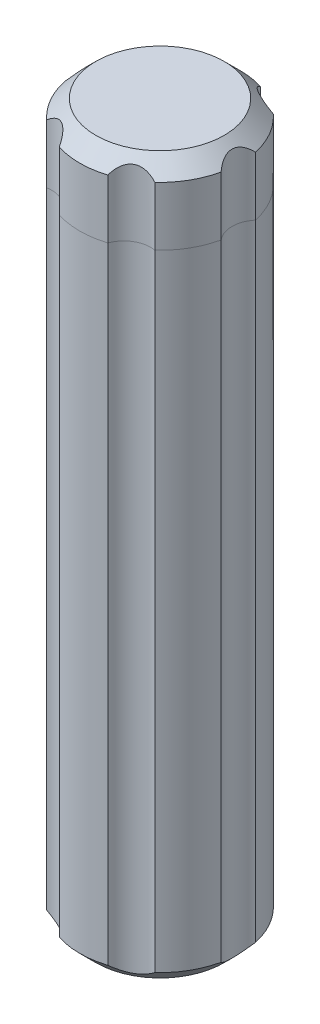
SolidWorks part; units mm, degrees
ref_plane "Front Plane" through (0, 0, 0) normal (0, 0, 1) x (1, 0, 0)
ref_plane "Top Plane" through (0, 0, 0) normal (0, 1, 0) x (1, 0, 0)
ref_plane "Right Plane" through (0, 0, 0) normal (1, 0, 0) x (0, 0, -1)
sketch "Sketch1" plane through (0, 0, 0) normal (0, 1, 0) x (1, 0, 0)
  circle A0 centre (0, 0) radius 7.5
  dimension "D1" = 15
extrude "Boss-Extrude1" add sketch "Sketch1" along normal blind 60
sketch "Sketch2" plane through (0, 60, 0) normal (0, 1, 0) x (1, 0, 0)
  circle A0 centre (0, 0) radius 6.1
  dimension "D1" = 12.2
extrude "Cut-Extrude1" cut sketch "Sketch2" against normal blind 58
sketch "Sketch3" plane through (0, 0, 0) normal (0, 0, 1) x (1, 0, 0)
  line L0 (-7.5, 0) -> (7.5, 0) construction
  circle A0 centre (0, 32) radius 3.5
  point P4 (0, 0)
  dimension "D1" = 7
  dimension "D2" = 32
extrude "Cut-Extrude2" cut sketch "Sketch3" against normal through all
sketch "Sketch4" plane through (0, 60, 0) normal (0, 1, 0) x (1, 0, 0)
  circle A0 centre (0, 0) radius 7.5
extrude "Boss-Extrude2" add sketch "Sketch4" along normal blind 7 separate body
sketch "Sketch5" plane through (0, 60, 0) normal (0, -1, 0) x (1, 0, 0)
  line L1 (2.9156, 5.05) -> (-2.9156, 5.05)
  line L2 (-2.9156, 5.05) -> (-5.8312, 0)
  line L3 (-5.8312, 0) -> (-2.9156, -5.05)
  line L4 (-2.9156, -5.05) -> (2.9156, -5.05)
  line L5 (2.9156, -5.05) -> (5.8312, 0)
  line L6 (5.8312, 0) -> (2.9156, 5.05)
  circle A0 centre (0, 0) radius 5.05 construction
  dimension "D1" = 10.1
extrude "Cut-Extrude3" cut sketch "Sketch5" against normal blind 4
chamfer "Chamfer1" distance 1.5 angle 45 1 edges at (0, 0, 7.5)
chamfer "Chamfer2" distance 1.5 angle 45 1 edges at (0, 67, 7.5)
sketch "Sketch7" plane through (0, 67, 0) normal (0, 1, 0) x (1, 0, 0)
  line L1 (4.6188, 8) -> (-4.6188, 8)
  line L2 (-4.6188, 8) -> (-9.2376, 0)
  line L3 (-9.2376, 0) -> (-4.6188, -8)
  line L4 (-4.6188, -8) -> (4.6188, -8)
  line L5 (4.6188, -8) -> (9.2376, 0)
  line L6 (9.2376, 0) -> (4.6188, 8)
  circle A0 centre (0, 0) radius 8 construction
  circle A1 centre (-9.2376, 0) radius 2.5
  circle A2 centre (-4.6188, 8) radius 2.5
  circle A3 centre (4.6188, 8) radius 2.5
  circle A4 centre (9.2376, 0) radius 2.5
  circle A5 centre (4.6188, -8) radius 2.5
  circle A6 centre (-4.6188, -8) radius 2.5
  dimension "D1" = 16
  dimension "D2" = 5
extrude "Cut-Extrude4" cut sketch "Sketch7" against normal blind 67 contours L2 A2 L1 | L3 A1 L2 | L4 A6 L3 | L5 A5 L4 | L6 A4 L5 | L1 A3 L6
